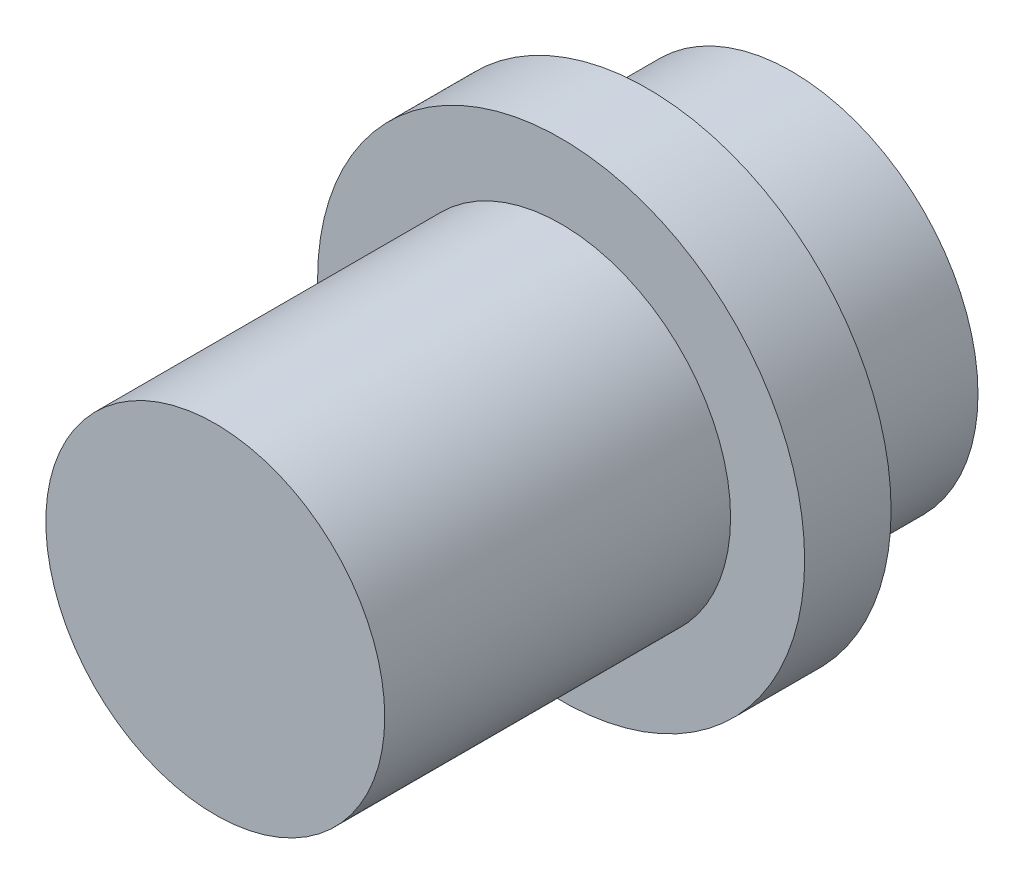
SolidWorks part; units mm, degrees
material "Custom Plastic"
ref_plane "X-Y Datum" through (0, 0, 0) normal (0, 0, 1) x (1, 0, 0)
ref_plane "X-Z Datum" through (0, 0, 0) normal (0, 1, 0) x (1, 0, 0)
ref_plane "Y-Z Datum" through (0, 0, 0) normal (1, 0, 0) x (0, 0, -1)
sketch "Sketch1" plane through (0, 0, 0) normal (0, 0, 1) x (1, 0, 0)
  circle A0 centre (0, 0) radius 5.88
  dimension "D1" = 11.76
extrude "Boss-Extrude1" add sketch "Sketch1" along normal blind 12
sketch "Sketch2" plane through (0, 0, 0) normal (0, 0, -1) x (-1, 0, 0)
  circle A0 centre (0, 0) radius 8.45
  dimension "D1" = 16.9
extrude "Boss-Extrude2" add sketch "Sketch2" along normal blind 3
sketch "Sketch3" plane through (0, 0, -3) normal (0, 0, -1) x (-1, 0, 0)
  circle A0 centre (0, 0) radius 6.465
  dimension "D1" = 12.93
extrude "Boss-Extrude3" add sketch "Sketch3" along normal blind 5
